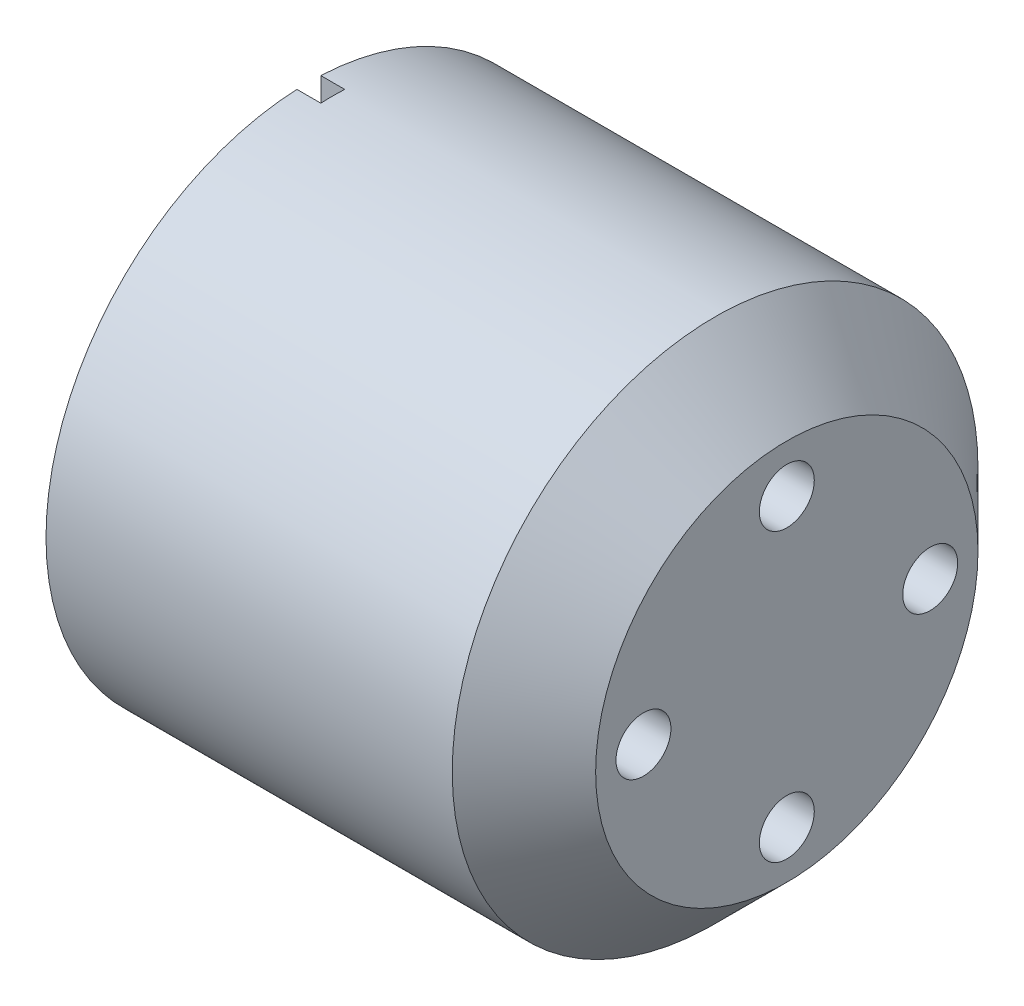
SolidWorks part; units mm, degrees
ref_plane "Front Plane" through (0, 0, 0) normal (0, 0, 1) x (1, 0, 0)
ref_plane "Top Plane" through (0, 0, 0) normal (0, 1, 0) x (1, 0, 0)
ref_plane "Right Plane" through (0, 0, 0) normal (1, 0, 0) x (0, 0, -1)
sketch "Sketch2" plane through (0, 0, 0) normal (1, 0, 0) x (0, 0, -1)
  circle A0 centre (0, 0) radius 11
  circle A1 centre (0, 0) radius 6 construction
  circle A2 centre (0, 6) radius 1.15
  circle A3 centre (-6, 0) radius 1.15
  circle A4 centre (0, -6) radius 1.15
  circle A5 centre (6, 0) radius 1.15
  dimension "D1" = 12
  dimension "D2" = 22
  dimension "D3" = 2.3
extrude "Boss-Extrude1" add sketch "Sketch2" along normal blind 20
chamfer "Chamfer1" distance 3 1 edges at (20, 0, -11)
sketch "Sketch5" plane through (0, 0, 0) normal (-1, 0, 0) x (0, 0, 1)
  circle A0 centre (-6, 0) radius 2
  circle A1 centre (0, 6) radius 2
  circle A2 centre (0, -6) radius 2
  circle A3 centre (6, 0) radius 2
  dimension "D1" = 4
extrude "Cut-Extrude2" cut sketch "Sketch5" against normal offset from surface (14.5 mm away) 5.5 up to face at (20, 0, -8)
sketch "Sketch6" plane through (0, 0, 0) normal (-1, 0, 0) x (0, 0, 1)
  line L0 (-5.3033, -5.3033) -> (5.3033, 5.3033) construction
  line L1 (-5.3033, 5.3033) -> (5.3033, -5.3033) construction
  line L2 (0, 7.5) -> (0, 0) construction
  circle A0 centre (0, 0) radius 7.5 construction
  circle A1 centre (5.3033, 5.3033) radius 2
  circle A2 centre (-5.3033, 5.3033) radius 2
  circle A3 centre (-5.3033, -5.3033) radius 2
  circle A4 centre (5.3033, -5.3033) radius 2
  dimension "D1" = 15
  dimension "D3" = 4
  dimension "D2" = 45
extrude "Cut-Extrude3" cut sketch "Sketch6" against normal blind 8
chamfer "Chamfer2" distance 0.3 distance2 1.2 4 edges at (0, -5.3033, -3.3033) (0, -5.3033, 7.3033) (0, 5.3033, 7.3033) (0, 5.3033, -3.3033)
sketch "Sketch7" plane through (0, 0, 0) normal (-1, 0, 0) x (0, 0, 1)
  line L0 (0, 0) -> (0, 11) construction
  line L2 (-0.5, 12.5) -> (0.5, 12.5)
  line L3 (-0.5, 12.5) -> (-0.5, 9.5)
  line L4 (-0.5, 9.5) -> (0.5, 9.5)
  line L5 (0.5, 12.5) -> (0.5, 9.5)
  line L6 (-0.5, 12.5) -> (0.5, 9.5) construction
  line L7 (-0.5, 9.5) -> (0.5, 12.5) construction
  circle A0 centre (0, 0) radius 11 construction
  dimension "D1" = 1
  dimension "D2" = 1.5
extrude "Cut-Extrude4" cut sketch "Sketch7" against normal blind 1
